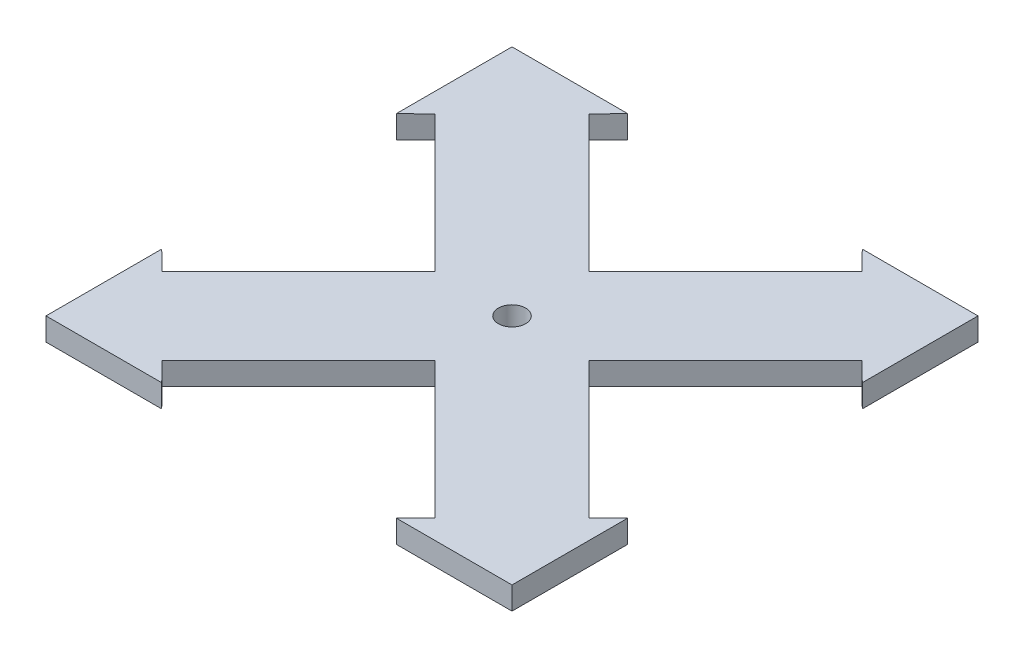
SolidWorks part; units mm, degrees
ref_plane "Front" through (0, 0, 0) normal (0, 0, 1) x (1, 0, 0)
ref_plane "Top" through (0, 0, 0) normal (0, 1, 0) x (1, 0, 0)
ref_plane "Right" through (0, 0, 0) normal (1, 0, 0) x (0, 0, -1)
sketch "Croquis1" plane through (0, 0, 0) normal (0, 1, 0) x (1, 0, 0)
  line L0 (-1000, 0) -> (49000, 0) construction
  line L1 (0, -1000) -> (0, 49000) construction
  line L2 (-707.1068, 707.1068) -> (34648.2323, -34648.2323) construction
  line L3 (-707.1068, -707.1068) -> (34648.2323, 34648.2323) construction
  line L4 (-15, -23.4853) -> (0, -8.4853)
  line L6 (8.4853, 0) -> (23.4853, -15)
  line L8 (-23.4853, -15) -> (-8.4853, 0)
  line L10 (-15, 23.4853) -> (0, 8.4853)
  line L12 (-1000, -15) -> (49000, -15) construction
  line L13 (-1000, 15) -> (49000, 15) construction
  line L14 (15, -1000) -> (15, 49000) construction
  line L15 (-15, -1000) -> (-15, 49000) construction
  line L16 (23.4853, -985) -> (23.4853, 49015) construction
  line L17 (-683.4111, 721.9431) -> (34671.9279, -34633.396) construction
  line L18 (15, 23.4853) -> (12.9022, 25.6298)
  line L19 (23.4853, 15) -> (25.6298, 12.9022)
  line L20 (-987.0978, 25.6298) -> (49012.9022, 25.6298) construction
  line L21 (25.6298, -987.1226) -> (25.6298, 49012.8774) construction
  line L22 (12.9022, 25.6298) -> (25.6298, 25.6298)
  line L23 (25.6298, 25.6298) -> (25.6298, 12.9022)
  line L24 (23.4853, -15) -> (25.6298, -12.9022)
  line L25 (25.6298, -12.9022) -> (25.6298, -25.6298)
  line L26 (25.6298, -25.6298) -> (12.9022, -25.6298)
  line L27 (15, -23.4853) -> (12.9022, -25.6298)
  line L28 (-15, -23.4853) -> (-12.9022, -25.6298)
  line L29 (-12.9022, -25.6298) -> (-25.6298, -25.6298)
  line L30 (-25.6298, -25.6298) -> (-25.6298, -12.9022)
  line L31 (-23.4853, -15) -> (-25.6298, -12.9022)
  line L32 (-23.4853, 15) -> (-25.6298, 12.9022)
  line L33 (-25.6298, 12.9022) -> (-25.6298, 25.6298)
  line L34 (-25.6298, 25.6298) -> (-12.9022, 25.6298)
  line L35 (-15, 23.4853) -> (-12.9022, 25.6298)
  line L36 (-23.4853, 15) -> (-8.4853, 0)
  line L37 (-702.8641, 711.3494) -> (34652.4749, -34643.9896) construction
  line L38 (-702.8641, -711.3494) -> (34652.4749, 34643.9896) construction
  line L39 (-711.3494, -702.8641) -> (34643.9896, 34652.4749) construction
  line L40 (0, 8.4853) -> (15, 23.4853)
  line L41 (0, -8.4853) -> (15, -23.4853)
  line L42 (8.4853, 0) -> (23.4853, 15)
  circle A0 centre (0, 0) radius 1.5
  point P11 (0, 0)
  point P12 (0, 0)
  point P13 (-711.3494, 702.8641)
  point P14 (34643.9896, -34652.4749)
  point P65 (0, 0)
  point P69 (-40.1286, 10.4651)
  dimension "D3" = 3
  dimension "D1" = 6
  dimension "D8" = 3
  dimension "D2" = 6
  dimension "D4" = 15
  dimension "D5" = 15
  dimension "D6" = 15
  dimension "D7" = 15
  dimension "D9" = 4
extrude "Saliente-Extruir1" add sketch "Croquis1" along normal blind 2.5
